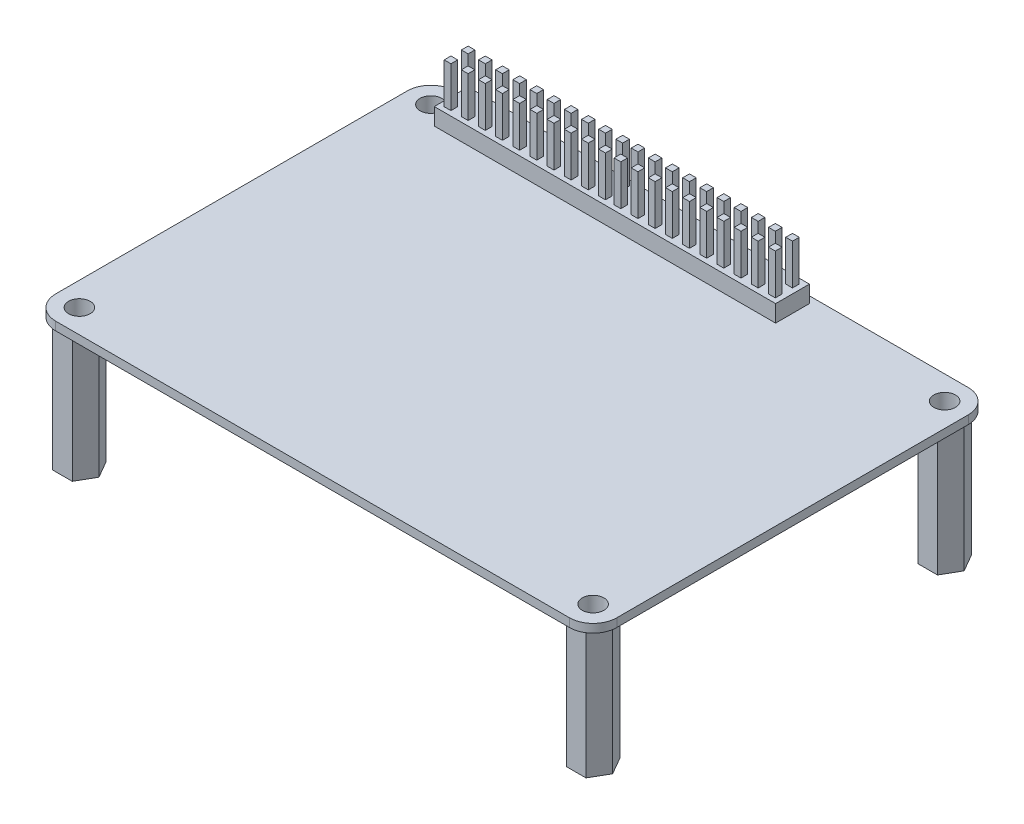
SolidWorks part; units mm, degrees
ref_plane "Plan de face" through (0, 0, 0) normal (0, 0, 1) x (1, 0, 0)
ref_plane "Plan de dessus" through (0, 0, 0) normal (0, 1, 0) x (1, 0, 0)
ref_plane "Plan de droite" through (0, 0, 0) normal (1, 0, 0) x (0, 0, -1)
sketch "Esquisse1" plane through (0, 0, 0) normal (0, 1, 0) x (1, 0, 0)
  line L1 (-38, -29.5) -> (38, -29.5)
  line L2 (-41.5, -26) -> (-41.5, 26)
  line L3 (-38, 29.5) -> (38, 29.5)
  line L4 (41.5, -26) -> (41.5, 26)
  line L5 (-41.5, -29.5) -> (41.5, 29.5) construction
  line L6 (-41.5, 29.5) -> (41.5, -29.5) construction
  arc A0 (-38, -29.5) -> (-41.5, -26) centre (-38, -26) cw
  arc A1 (38, -29.5) -> (41.5, -26) centre (38, -26) ccw
  arc A2 (38, 29.5) -> (41.5, 26) centre (38, 26) cw
  arc A3 (-41.5, 26) -> (-38, 29.5) centre (-38, 26) cw
  circle A4 centre (38, 26) radius 1.6
  circle A5 centre (38, -26) radius 1.6
  circle A6 centre (-38, 26) radius 1.6
  circle A7 centre (-38, -26) radius 1.6
  point P0 (0, 0)
  dimension "D3" = 3.5
  dimension "D4" = 3.2
  dimension "D5" = 3.2
  dimension "D6" = 3.2
  dimension "D7" = 3.2
  dimension "D1" = 83
  dimension "D2" = 59
extrude "Boss.-Extru.1" add sketch "Esquisse1" along normal blind 1.25
sketch "Esquisse2" plane through (0, 0, 0) normal (0, -1, 0) x (1, 0, 0)
  line L0 (-38, 29.5) -> (38, 29.5) construction
  line L1 (-36.5566, 28.5) -> (-39.4434, 28.5)
  line L2 (-39.4434, 28.5) -> (-40.8868, 26)
  line L3 (-40.8868, 26) -> (-39.4434, 23.5)
  line L4 (-39.4434, 23.5) -> (-36.5566, 23.5)
  line L5 (-36.5566, 23.5) -> (-35.1132, 26)
  line L6 (-35.1132, 26) -> (-36.5566, 28.5)
  line L7 (38, -29.5) -> (-38, -29.5) construction
  line L8 (-36.5566, -23.5) -> (-39.4434, -23.5)
  line L9 (-39.4434, -23.5) -> (-40.8868, -26)
  line L10 (-40.8868, -26) -> (-39.4434, -28.5)
  line L11 (-39.4434, -28.5) -> (-36.5566, -28.5)
  line L12 (-36.5566, -28.5) -> (-35.1132, -26)
  line L13 (-35.1132, -26) -> (-36.5566, -23.5)
  line L14 (39.4434, -23.5) -> (36.5566, -23.5)
  line L15 (36.5566, -23.5) -> (35.1132, -26)
  line L16 (35.1132, -26) -> (36.5566, -28.5)
  line L17 (36.5566, -28.5) -> (39.4434, -28.5)
  line L18 (39.4434, -28.5) -> (40.8868, -26)
  line L19 (40.8868, -26) -> (39.4434, -23.5)
  line L20 (36.5566, 23.5) -> (39.4434, 23.5)
  line L21 (39.4434, 23.5) -> (40.8868, 26)
  line L22 (40.8868, 26) -> (39.4434, 28.5)
  line L23 (39.4434, 28.5) -> (36.5566, 28.5)
  line L24 (36.5566, 28.5) -> (35.1132, 26)
  line L25 (35.1132, 26) -> (36.5566, 23.5)
  circle A0 centre (-38, 26) radius 2.5 construction
  circle A1 centre (-38, -26) radius 2.5 construction
  circle A2 centre (38, -26) radius 2.5 construction
  circle A3 centre (38, 26) radius 2.5 construction
  circle A4 centre (-38, 26) radius 1.6
  circle A5 centre (38, 26) radius 1.6
  circle A6 centre (38, -26) radius 1.6
  circle A7 centre (-38, -26) radius 1.6
  dimension "D1" = 5
  dimension "D2" = 5
  dimension "D3" = 5
  dimension "D4" = 5
  dimension "D5" = 3.2
  dimension "D6" = 3.2
  dimension "D7" = 3.2
  dimension "D8" = 3.2
extrude "Boss.-Extru.2" add sketch "Esquisse2" along normal blind 19.05
sketch "Esquisse4" plane through (0, 1.25, 0) normal (0, 1, 0) x (1, 0, 0)
  line L0 (38, 29.5) -> (-38, 29.5) construction
  line L1 (-35, 28.5) -> (15.5, 28.5)
  line L2 (-35, 28.5) -> (-35, 23.5)
  line L3 (-35, 23.5) -> (15.5, 23.5)
  line L4 (15.5, 28.5) -> (15.5, 23.5)
  line L5 (-35, 28.5) -> (15.5, 23.5) construction
  line L6 (-35, 23.5) -> (15.5, 28.5) construction
  line L7 (-41.5, 26) -> (-41.5, -26) construction
  point P0 (-9.75, 26)
  dimension "D1" = 50.5
  dimension "D2" = 5
  dimension "D3" = 1
  dimension "D4" = 6.5
extrude "Boss.-Extru.3" add sketch "Esquisse4" along normal blind 2.5
sketch "Esquisse5" plane through (0, 3.75, 0) normal (0, 1, 0) x (1, 0, 0)
  line L0 (-35, 26) -> (15.5, 26) construction
  line L1 (-35, 28.5) -> (-35, 23.5) construction
  line L2 (15.5, 23.5) -> (15.5, 28.5) construction
  line L3 (-9.75, 26) -> (-9.75, 28.5) construction
  line L4 (14.745, 27.75) -> (13.745, 27.75)
  line L5 (14.745, 27.75) -> (14.745, 26.75)
  line L6 (15.5, 28.5) -> (-35, 28.5) construction
  line L7 (-10.385, 27.75) -> (-11.385, 27.75)
  line L8 (-10.385, 27.75) -> (-10.385, 26.75)
  line L9 (-10.385, 26.75) -> (-11.385, 26.75)
  line L10 (-11.385, 27.75) -> (-11.385, 26.75)
  line L11 (-10.385, 27.75) -> (-11.385, 26.75) construction
  line L12 (-10.385, 26.75) -> (-11.385, 27.75) construction
  line L13 (-9.75, 27.25) -> (-35, 27.25) construction
  line L14 (-12.925, 26.75) -> (-13.925, 26.75)
  line L15 (-12.925, 27.75) -> (-13.925, 27.75)
  line L16 (-13.925, 27.75) -> (-13.925, 26.75)
  line L17 (-12.925, 27.75) -> (-12.925, 26.75)
  line L18 (-15.465, 26.75) -> (-16.465, 26.75)
  line L19 (-15.465, 27.75) -> (-16.465, 27.75)
  line L20 (-16.465, 27.75) -> (-16.465, 26.75)
  line L21 (-15.465, 27.75) -> (-15.465, 26.75)
  line L22 (-18.005, 26.75) -> (-19.005, 26.75)
  line L23 (-18.005, 27.75) -> (-19.005, 27.75)
  line L24 (-19.005, 27.75) -> (-19.005, 26.75)
  line L25 (-18.005, 27.75) -> (-18.005, 26.75)
  line L26 (-20.545, 26.75) -> (-21.545, 26.75)
  line L27 (-20.545, 27.75) -> (-21.545, 27.75)
  line L28 (-21.545, 27.75) -> (-21.545, 26.75)
  line L29 (-20.545, 27.75) -> (-20.545, 26.75)
  line L30 (-23.085, 26.75) -> (-24.085, 26.75)
  line L31 (-23.085, 27.75) -> (-24.085, 27.75)
  line L32 (-24.085, 27.75) -> (-24.085, 26.75)
  line L33 (-23.085, 27.75) -> (-23.085, 26.75)
  line L34 (-25.625, 26.75) -> (-26.625, 26.75)
  line L35 (-25.625, 27.75) -> (-26.625, 27.75)
  line L36 (-26.625, 27.75) -> (-26.625, 26.75)
  line L37 (-25.625, 27.75) -> (-25.625, 26.75)
  line L38 (-28.165, 26.75) -> (-29.165, 26.75)
  line L39 (-28.165, 27.75) -> (-29.165, 27.75)
  line L40 (-29.165, 27.75) -> (-29.165, 26.75)
  line L41 (-28.165, 27.75) -> (-28.165, 26.75)
  line L42 (-30.705, 26.75) -> (-31.705, 26.75)
  line L43 (-30.705, 27.75) -> (-31.705, 27.75)
  line L44 (-31.705, 27.75) -> (-31.705, 26.75)
  line L45 (-30.705, 27.75) -> (-30.705, 26.75)
  line L46 (-33.245, 26.75) -> (-34.245, 26.75)
  line L47 (-33.245, 27.75) -> (-34.245, 27.75)
  line L48 (-34.245, 27.75) -> (-34.245, 26.75)
  line L49 (-33.245, 27.75) -> (-33.245, 26.75)
  line L50 (14.745, 26.75) -> (13.745, 26.75)
  line L51 (13.745, 27.75) -> (13.745, 26.75)
  line L52 (12.205, 26.75) -> (11.205, 26.75)
  line L53 (12.205, 27.75) -> (11.205, 27.75)
  line L54 (11.205, 27.75) -> (11.205, 26.75)
  line L55 (12.205, 27.75) -> (12.205, 26.75)
  line L56 (9.665, 26.75) -> (8.665, 26.75)
  line L57 (9.665, 27.75) -> (8.665, 27.75)
  line L58 (8.665, 27.75) -> (8.665, 26.75)
  line L59 (9.665, 27.75) -> (9.665, 26.75)
  line L60 (7.125, 26.75) -> (6.125, 26.75)
  line L61 (7.125, 27.75) -> (6.125, 27.75)
  line L62 (6.125, 27.75) -> (6.125, 26.75)
  line L63 (7.125, 27.75) -> (7.125, 26.75)
  line L64 (4.585, 26.75) -> (3.585, 26.75)
  line L65 (4.585, 27.75) -> (3.585, 27.75)
  line L66 (3.585, 27.75) -> (3.585, 26.75)
  line L67 (4.585, 27.75) -> (4.585, 26.75)
  line L68 (2.045, 26.75) -> (1.045, 26.75)
  line L69 (2.045, 27.75) -> (1.045, 27.75)
  line L70 (1.045, 27.75) -> (1.045, 26.75)
  line L71 (2.045, 27.75) -> (2.045, 26.75)
  line L72 (-0.495, 26.75) -> (-1.495, 26.75)
  line L73 (-0.495, 27.75) -> (-1.495, 27.75)
  line L74 (-1.495, 27.75) -> (-1.495, 26.75)
  line L75 (-0.495, 27.75) -> (-0.495, 26.75)
  line L76 (-3.035, 26.75) -> (-4.035, 26.75)
  line L77 (-3.035, 27.75) -> (-4.035, 27.75)
  line L78 (-4.035, 27.75) -> (-4.035, 26.75)
  line L79 (-3.035, 27.75) -> (-3.035, 26.75)
  line L80 (-5.575, 26.75) -> (-6.575, 26.75)
  line L81 (-5.575, 27.75) -> (-6.575, 27.75)
  line L82 (-6.575, 27.75) -> (-6.575, 26.75)
  line L83 (-5.575, 27.75) -> (-5.575, 26.75)
  line L84 (-8.115, 26.75) -> (-9.115, 26.75)
  line L85 (-8.115, 27.75) -> (-9.115, 27.75)
  line L86 (-9.115, 27.75) -> (-9.115, 26.75)
  line L87 (-8.115, 27.75) -> (-8.115, 26.75)
  line L88 (14.745, 27.75) -> (13.745, 26.75) construction
  line L89 (14.745, 26.75) -> (13.745, 27.75) construction
  line L90 (14.745, 25.21) -> (13.745, 25.21)
  line L91 (14.745, 25.21) -> (14.745, 24.21)
  line L92 (-10.385, 25.21) -> (-11.385, 25.21)
  line L93 (-10.385, 25.21) -> (-10.385, 24.21)
  line L94 (-10.385, 24.21) -> (-11.385, 24.21)
  line L95 (-11.385, 25.21) -> (-11.385, 24.21)
  line L96 (-12.925, 24.21) -> (-13.925, 24.21)
  line L97 (-12.925, 25.21) -> (-13.925, 25.21)
  line L98 (-13.925, 25.21) -> (-13.925, 24.21)
  line L99 (-12.925, 25.21) -> (-12.925, 24.21)
  line L100 (-15.465, 24.21) -> (-16.465, 24.21)
  line L101 (-15.465, 25.21) -> (-16.465, 25.21)
  line L102 (-16.465, 25.21) -> (-16.465, 24.21)
  line L103 (-15.465, 25.21) -> (-15.465, 24.21)
  line L104 (-18.005, 24.21) -> (-19.005, 24.21)
  line L105 (-18.005, 25.21) -> (-19.005, 25.21)
  line L106 (-19.005, 25.21) -> (-19.005, 24.21)
  line L107 (-18.005, 25.21) -> (-18.005, 24.21)
  line L108 (-20.545, 24.21) -> (-21.545, 24.21)
  line L109 (-20.545, 25.21) -> (-21.545, 25.21)
  line L110 (-21.545, 25.21) -> (-21.545, 24.21)
  line L111 (-20.545, 25.21) -> (-20.545, 24.21)
  line L112 (-23.085, 24.21) -> (-24.085, 24.21)
  line L113 (-23.085, 25.21) -> (-24.085, 25.21)
  line L114 (-24.085, 25.21) -> (-24.085, 24.21)
  line L115 (-23.085, 25.21) -> (-23.085, 24.21)
  line L116 (-25.625, 24.21) -> (-26.625, 24.21)
  line L117 (-25.625, 25.21) -> (-26.625, 25.21)
  line L118 (-26.625, 25.21) -> (-26.625, 24.21)
  line L119 (-25.625, 25.21) -> (-25.625, 24.21)
  line L120 (-28.165, 24.21) -> (-29.165, 24.21)
  line L121 (-28.165, 25.21) -> (-29.165, 25.21)
  line L122 (-29.165, 25.21) -> (-29.165, 24.21)
  line L123 (-28.165, 25.21) -> (-28.165, 24.21)
  line L124 (-30.705, 24.21) -> (-31.705, 24.21)
  line L125 (-30.705, 25.21) -> (-31.705, 25.21)
  line L126 (-31.705, 25.21) -> (-31.705, 24.21)
  line L127 (-30.705, 25.21) -> (-30.705, 24.21)
  line L128 (-33.245, 24.21) -> (-34.245, 24.21)
  line L129 (-33.245, 25.21) -> (-34.245, 25.21)
  line L130 (-34.245, 25.21) -> (-34.245, 24.21)
  line L131 (-33.245, 25.21) -> (-33.245, 24.21)
  line L132 (14.745, 24.21) -> (13.745, 24.21)
  line L133 (13.745, 25.21) -> (13.745, 24.21)
  line L134 (12.205, 24.21) -> (11.205, 24.21)
  line L135 (12.205, 25.21) -> (11.205, 25.21)
  line L136 (11.205, 25.21) -> (11.205, 24.21)
  line L137 (12.205, 25.21) -> (12.205, 24.21)
  line L138 (9.665, 24.21) -> (8.665, 24.21)
  line L139 (9.665, 25.21) -> (8.665, 25.21)
  line L140 (8.665, 25.21) -> (8.665, 24.21)
  line L141 (9.665, 25.21) -> (9.665, 24.21)
  line L142 (7.125, 24.21) -> (6.125, 24.21)
  line L143 (7.125, 25.21) -> (6.125, 25.21)
  line L144 (6.125, 25.21) -> (6.125, 24.21)
  line L145 (7.125, 25.21) -> (7.125, 24.21)
  line L146 (4.585, 24.21) -> (3.585, 24.21)
  line L147 (4.585, 25.21) -> (3.585, 25.21)
  line L148 (3.585, 25.21) -> (3.585, 24.21)
  line L149 (4.585, 25.21) -> (4.585, 24.21)
  line L150 (2.045, 24.21) -> (1.045, 24.21)
  line L151 (2.045, 25.21) -> (1.045, 25.21)
  line L152 (1.045, 25.21) -> (1.045, 24.21)
  line L153 (2.045, 25.21) -> (2.045, 24.21)
  line L154 (-0.495, 24.21) -> (-1.495, 24.21)
  line L155 (-0.495, 25.21) -> (-1.495, 25.21)
  line L156 (-1.495, 25.21) -> (-1.495, 24.21)
  line L157 (-0.495, 25.21) -> (-0.495, 24.21)
  line L158 (-3.035, 24.21) -> (-4.035, 24.21)
  line L159 (-3.035, 25.21) -> (-4.035, 25.21)
  line L160 (-4.035, 25.21) -> (-4.035, 24.21)
  line L161 (-3.035, 25.21) -> (-3.035, 24.21)
  line L162 (-5.575, 24.21) -> (-6.575, 24.21)
  line L163 (-5.575, 25.21) -> (-6.575, 25.21)
  line L164 (-6.575, 25.21) -> (-6.575, 24.21)
  line L165 (-5.575, 25.21) -> (-5.575, 24.21)
  line L166 (-8.115, 24.21) -> (-9.115, 24.21)
  line L167 (-8.115, 25.21) -> (-9.115, 25.21)
  line L168 (-9.115, 25.21) -> (-9.115, 24.21)
  line L169 (-8.115, 25.21) -> (-8.115, 24.21)
  line L170 (-9.75, 23.46) -> (-9.75, 25.96) construction
  line L171 (-10.385, 25.21) -> (-11.385, 24.21) construction
  line L172 (-10.385, 24.21) -> (-11.385, 25.21) construction
  line L173 (-9.75, 24.71) -> (-35, 24.71) construction
  line L174 (14.745, 25.21) -> (13.745, 24.21) construction
  line L175 (14.745, 24.21) -> (13.745, 25.21) construction
  point P12 (-10.885, 27.25)
  point P18 (14.245, 27.25)
  point P99 (-10.885, 24.71)
  point P104 (14.245, 24.71)
  dimension "D1" = 1
  dimension "D2" = 1
  dimension "D3" = 0.635
  dimension "D4" = 10
  dimension "D5" = 2.54
  dimension "D7" = 1.27
  dimension "D9" = 2.54
  dimension "D6" = 2
  dimension "D8" = 2
extrude "Boss.-Extru.4" add sketch "Esquisse5" along normal blind 6
